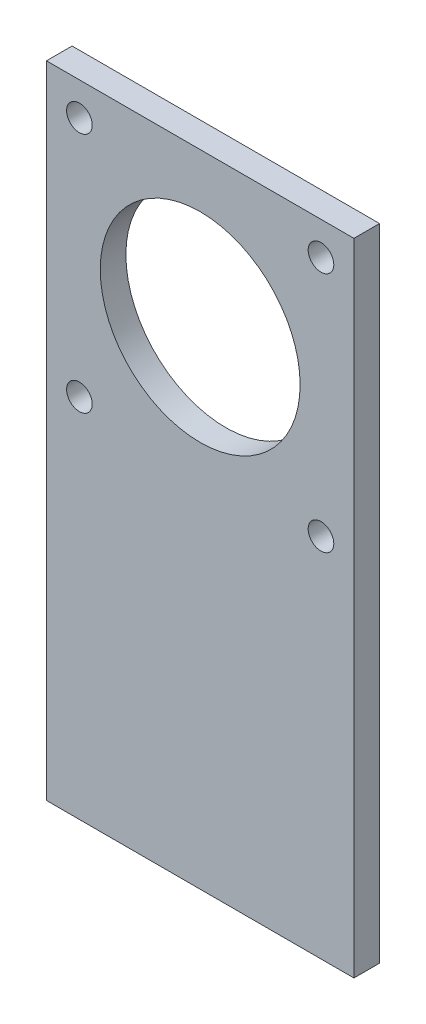
SolidWorks part; units mm, degrees
ref_plane "정면" through (0, 0, 0) normal (0, 0, 1) x (1, 0, 0)
ref_plane "윗면" through (0, 0, 0) normal (0, 1, 0) x (1, 0, 0)
ref_plane "우측면" through (0, 0, 0) normal (1, 0, 0) x (0, 0, -1)
sketch "스케치1" plane through (0, 0, 0) normal (0, 0, 1) x (1, 0, 0)
  line L1 (-30, 62.5) -> (30, 62.5)
  line L2 (-30, 62.5) -> (-30, -62.5)
  line L3 (-30, -62.5) -> (30, -62.5)
  line L4 (30, 62.5) -> (30, -62.5)
  line L5 (-30, 62.5) -> (30, -62.5) construction
  line L6 (-30, -62.5) -> (30, 62.5) construction
  point P0 (0, 0)
  dimension "D1" = 60
  dimension "D2" = 125
extrude "보스-돌출1" add sketch "스케치1" along normal blind 5
sketch "스케치4" plane through (0, 0, 0) normal (0, 0, -1) x (-1, 0, 0)
  line L3 (-30, 62.5) -> (30, 62.5) construction
  line L4 (30, 62.5) -> (30, -62.5) construction
  circle A0 centre (0, 32.5) radius 19.5
  point P6 (28.5, 30.3166)
  dimension "D1" = 39
  dimension "D3" = 30
  dimension "D2" = 30
extrude "컷-돌출2" cut sketch "스케치4" against normal blind 10
sketch "스케치2" plane through (0, 0, 5) normal (0, 0, 1) x (1, 0, 0)
  circle A10 centre (-23.57, 56.07) radius 5.8
  circle A11 centre (-23.57, 56.07) radius 2.5
  circle A12 centre (23.57, 56.07) radius 5.8
  circle A13 centre (23.57, 56.07) radius 2.5
  circle A14 centre (-23.57, 8.93) radius 5.8
  circle A15 centre (-23.57, 8.93) radius 2.5
  circle A16 centre (23.57, 8.93) radius 5.8
  circle A17 centre (23.57, 8.93) radius 2.5
  circle A18 centre (0, 32.5) radius 19.5 construction
  point P14 (0, 0)
  point P15 (0, 0)
  point P16 (22.4318, 55.0905)
  point P17 (0, 0)
  dimension "D3" = 5
  dimension "D4" = 11.6
  dimension "D5" = 5
  dimension "D8" = 11.6
  dimension "D9" = 11.6
  dimension "D10" = 47.14
  dimension "D11" = 23.57
  dimension "D12" = 23.57
  dimension "D13" = 23.57
  dimension "D2" = 11.6
  dimension "D6" = 5
  dimension "D7" = 5
  dimension "D16" = 23.57
  dimension "D17" = 47.14
extrude "컷-돌출1" cut sketch "스케치2" against normal blind 5 contours A13 | A17 | A15 | A11
